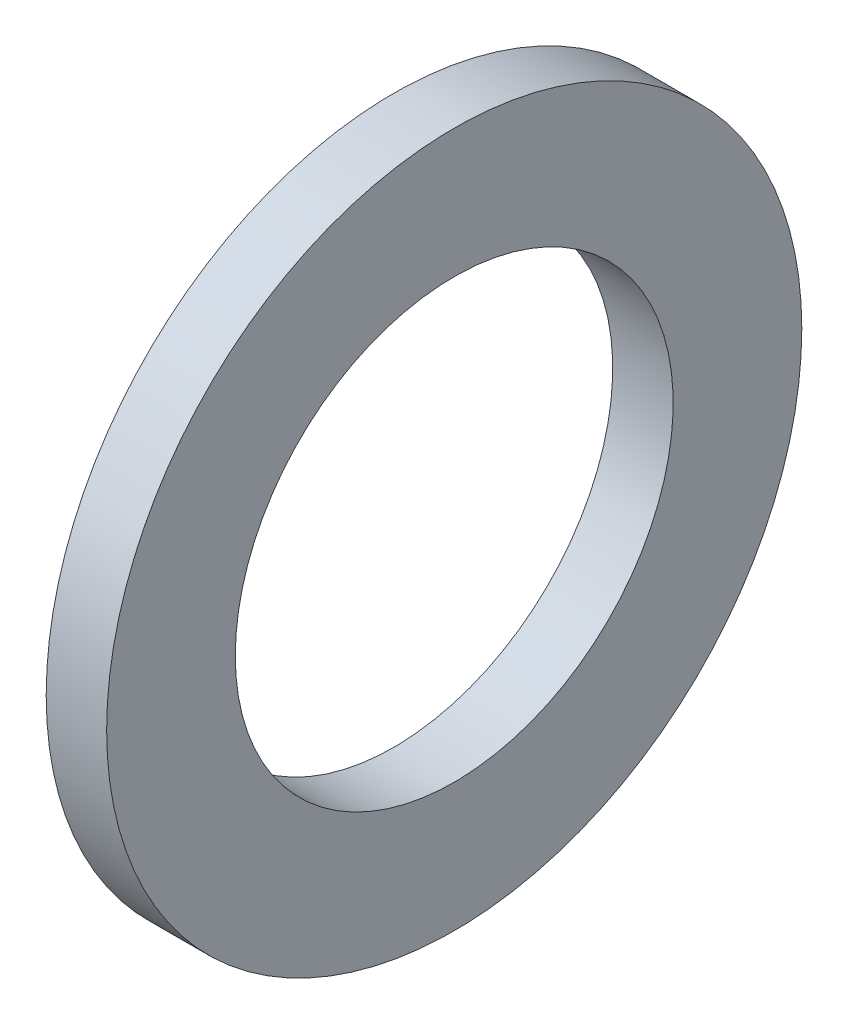
SolidWorks part; units mm, degrees
material "Plain Carbon Steel"
ref_plane "Plane1" through (0, 0, 0) normal (0, 0, 1) x (1, 0, 0)
ref_plane "Plane2" through (0, 0, 0) normal (0, 1, 0) x (1, 0, 0)
ref_plane "Plane3" through (0, 0, 0) normal (1, 0, 0) x (0, 0, -1)
sketch "Sketch1" plane through (0, 0, 0) normal (0, 0, 1) x (1, 0, 0)
  line L0 (-34.925, 0) -> (9.525, 0) construction
  line L1 (0, 1.84) -> (0, 2.921)
  line L2 (0, 2.921) -> (-0.508, 2.921)
  line L3 (-0.508, 2.921) -> (-0.508, 1.84)
  line L4 (-0.508, 1.84) -> (0, 1.84)
  dimension "Thickness" = 0.508
  dimension "Inside_dia" = 3.68
  dimension "Outside_dia" = 5.842
revolve "Base-Revolve" add sketch "Sketch1" angle 360 about L0
